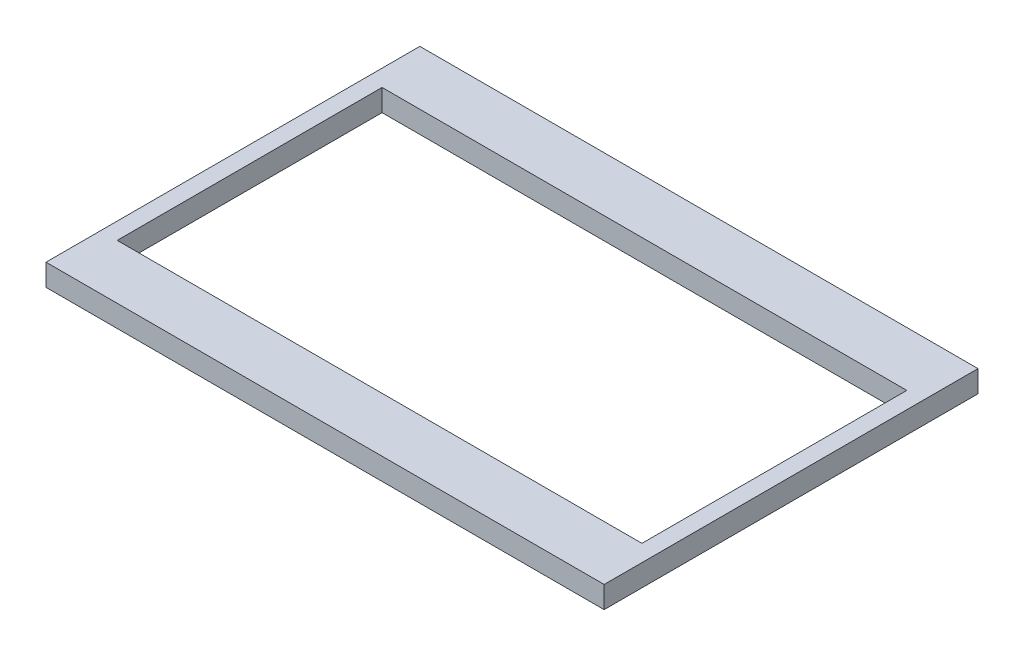
SolidWorks part; units mm, degrees
ref_plane "Front Plane" through (0, 0, 0) normal (0, 0, 1) x (1, 0, 0)
ref_plane "Top Plane" through (0, 0, 0) normal (0, 1, 0) x (1, 0, 0)
ref_plane "Right Plane" through (0, 0, 0) normal (1, 0, 0) x (0, 0, -1)
sketch "Sketch1" plane through (0, 0, 0) normal (0, 1, 0) x (1, 0, 0)
  line L5 (63.9, -42.8) -> (-63.9, -42.8)
  line L6 (63.9, -42.8) -> (63.9, 42.8)
  line L11 (63.9, 42.8) -> (-63.9, 42.8)
  line L12 (-63.9, -42.8) -> (-63.9, 42.8)
  line L13 (63.9, -42.8) -> (-63.9, 42.8) construction
  line L14 (63.9, 42.8) -> (-63.9, -42.8) construction
  point P0 (0, 0)
  dimension "D1" = 127.8
  dimension "D2" = 85.6
extrude "Boss-Extrude1" add sketch "Sketch1" along normal blind 5
sketch "Sketch2" plane through (0, 5, 0) normal (0, 1, 0) x (1, 0, 0)
  line L1 (60.075, -30.325) -> (-60.075, -30.325)
  line L2 (60.075, -30.325) -> (60.075, 30.325)
  line L3 (60.075, 30.325) -> (-60.075, 30.325)
  line L4 (-60.075, -30.325) -> (-60.075, 30.325)
  line L5 (60.075, -30.325) -> (-60.075, 30.325) construction
  line L6 (60.075, 30.325) -> (-60.075, -30.325) construction
  point P0 (0, 0)
  dimension "D1" = 120.15
  dimension "D2" = 60.65
extrude "Cut-Extrude1" cut sketch "Sketch2" against normal blind 5
